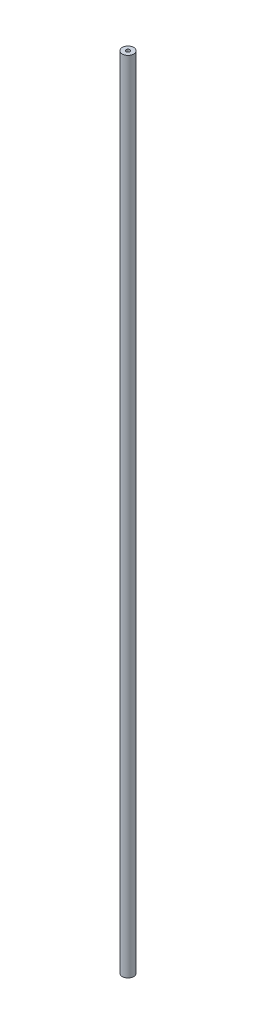
SolidWorks part; units mm, degrees
ref_plane "Front Plane" through (0, 0, 0) normal (0, 0, 1) x (1, 0, 0)
ref_plane "Top Plane" through (0, 0, 0) normal (0, 1, 0) x (1, 0, 0)
ref_plane "Right Plane" through (0, 0, 0) normal (1, 0, 0) x (0, 0, -1)
sketch "Sketch1" plane through (0, 0, 0) normal (0, 1, 0) x (1, 0, 0)
  circle A0 centre (0, 0) radius 7.9375
  dimension "D1" = 15.875
extrude "Boss-Extrude1" add sketch "Sketch1" along normal blind 1104.9
hole_wizard "1/4-20 Tapped Hole1" positions "Sketch2" profile "Sketch4" tap size "1/4-20" standard "ANSI Inch"
sketch "Sketch2" plane through (0, 1104.9, 0) normal (0, 1, 0) x (1, 0, 0)
  point P0 (0, 0)
sketch "Sketch4" plane through (0, 1104.9, 0) normal (1, 0, 0) x (0, 0, 1)
  line L0 (0, 0) -> (0, 25.4)
  line L1 (0, 25.4) -> (2.5527, 23.8662)
  line L2 (2.5527, 23.8662) -> (2.5527, 0)
  line L5 (2.5527, 0) -> (0, 0)
  line L10 (0, 25.4) -> (-2.5527, 23.8662) construction
  line L11 (0, -6.35) -> (0, 107.95) construction
  dimension "Tap Drill Dia." = 5.1054
  dimension "Tap Drill Depth" = 25.4
  dimension "Drill Angle" = 118
